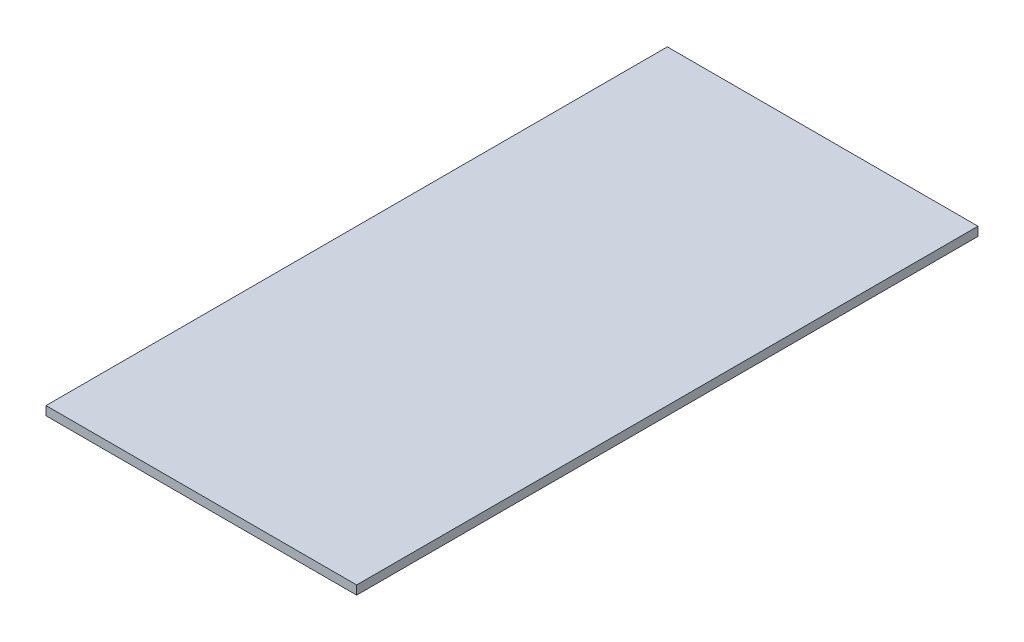
SolidWorks part; units mm, degrees
ref_plane "Front Plane" through (0, 0, 0) normal (0, 0, 1) x (1, 0, 0)
ref_plane "Top Plane" through (0, 0, 0) normal (0, 1, 0) x (1, 0, 0)
ref_plane "Right Plane" through (0, 0, 0) normal (1, 0, 0) x (0, 0, -1)
sketch "Sketch1" plane through (0, 0, 0) normal (0, 1, 0) x (1, 0, 0)
  line L1 (-5, -10) -> (5, -10)
  line L2 (-5, -10) -> (-5, 10)
  line L3 (-5, 10) -> (5, 10)
  line L4 (5, -10) -> (5, 10)
  line L5 (-5, -10) -> (5, 10) construction
  line L6 (-5, 10) -> (5, -10) construction
  point P0 (0, 0)
  dimension "D1" = 10
  dimension "D2" = 20
extrude "Boss-Extrude1" add sketch "Sketch1" along normal blind 0.285
